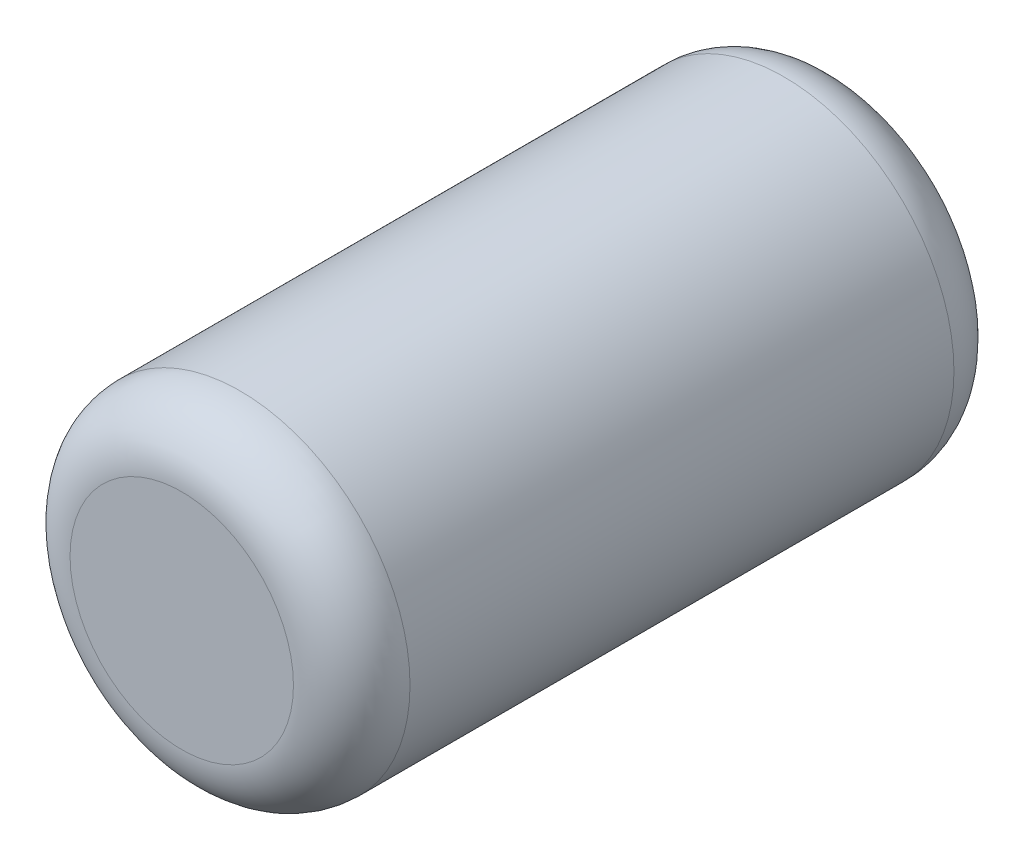
SolidWorks part; units mm, degrees
ref_plane "Front Plane" through (0, 0, 0) normal (0, 0, 1) x (1, 0, 0)
ref_plane "Top Plane" through (0, 0, 0) normal (0, 1, 0) x (1, 0, 0)
ref_plane "Right Plane" through (0, 0, 0) normal (1, 0, 0) x (0, 0, -1)
sketch "Sketch2" plane through (0, 0, 0) normal (0, 0, 1) x (1, 0, 0)
  circle A0 centre (0, 0) radius 8.75
  dimension "D1" = 17.5
extrude "Boss-Extrude1" add sketch "Sketch2" along normal blind 34
ref_point "Point1"
ref_point "Point2"
fillet "Fillet1" radius 3 2 edges at (8.75, 0, 34) (8.75, 0, 0)
